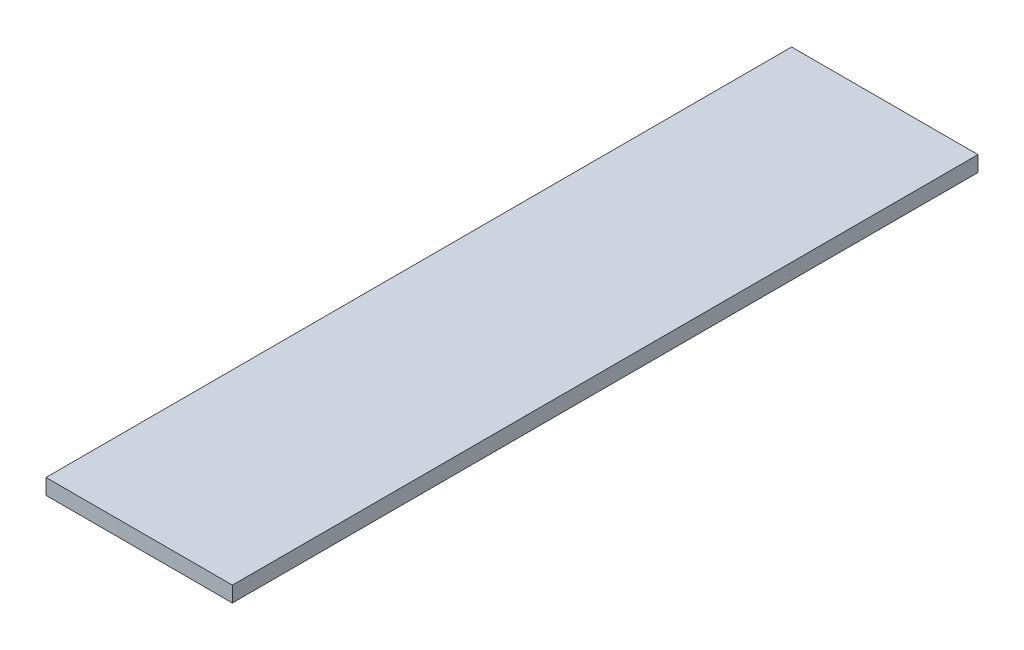
SolidWorks part; units mm, degrees
ref_plane "Front Plane" through (0, 0, 0) normal (0, 0, 1) x (1, 0, 0)
ref_plane "Top Plane" through (0, 0, 0) normal (0, 1, 0) x (1, 0, 0)
ref_plane "Right Plane" through (0, 0, 0) normal (1, 0, 0) x (0, 0, -1)
sketch "Sketch1" plane through (0, 0, 0) normal (0, 0, 1) x (1, 0, 0)
  line L1 (-38.1, -38.1) -> (38.1, -38.1)
  line L2 (-38.1, -38.1) -> (-38.1, 38.1)
  line L3 (-38.1, 38.1) -> (38.1, 38.1)
  line L4 (38.1, -38.1) -> (38.1, 38.1)
  line L5 (-38.1, -38.1) -> (38.1, 38.1) construction
  line L6 (-38.1, 38.1) -> (38.1, -38.1) construction
  line L7 (-38.1, 38.1) -> (38.1, 38.1)
  line L8 (-38.1, 38.1) -> (-38.1, 44.45)
  line L9 (-38.1, 44.45) -> (38.1, 44.45)
  line L10 (38.1, 38.1) -> (38.1, 44.45)
  point P0 (0, 0)
  dimension "D1" = 76.2
  dimension "D2" = 6.35
extrude "Boss-Extrude1" add sketch "Sketch1" along normal blind 304.8 contours L3 L10 L9 L8
